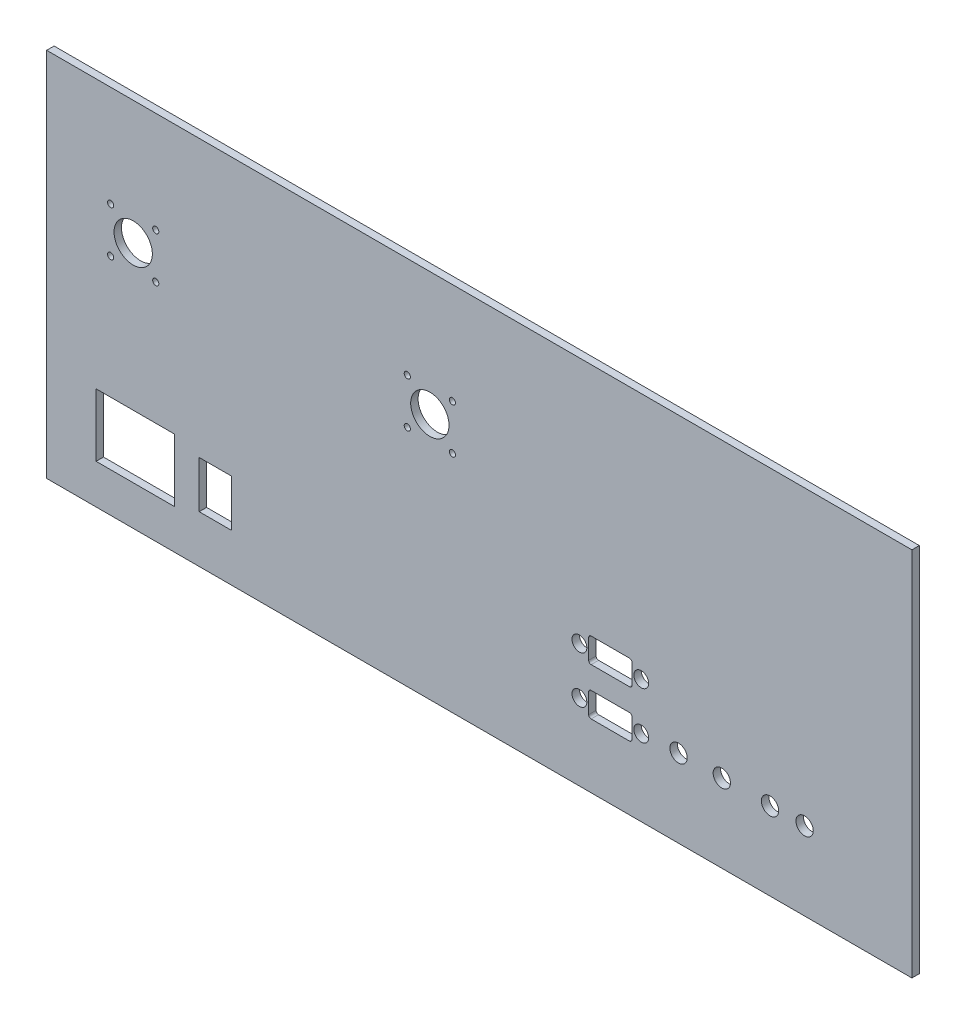
SolidWorks part; units mm, degrees
ref_plane "前视基准面" through (0, 0, 0) normal (0, 0, 1) x (1, 0, 0)
ref_plane "上视基准面" through (0, 0, 0) normal (0, 1, 0) x (1, 0, 0)
ref_plane "右视基准面" through (0, 0, 0) normal (1, 0, 0) x (0, 0, -1)
sketch "草图2" plane through (0, 0, 0) normal (0, 0, 1) x (1, 0, 0)
  line L4 (-175, 150) -> (-175, 0)
  line L5 (-175, 0) -> (175, 0)
  line L6 (175, 0) -> (175, 150)
  line L7 (175, 150) -> (-175, 150)
  line L8 (-175, 150) -> (-175, 0)
  line L9 (-175, 0) -> (175, 0)
  line L10 (175, 0) -> (175, 150)
  line L11 (175, 150) -> (-175, 150)
  dimension "D1" = 0
extrude "凸台-拉伸1" add sketch "草图2" along normal blind 3
sketch "草图3" plane through (0, 0, 3) normal (0, 0, 1) x (1, 0, 0)
  line L0 (37, 24.6) -> (137, 24.6) construction
  line L1 (-155, 28.7) -> (-106.8, 28.7) construction
  line L2 (36.8578, 25.7694) -> (54.3578, 35.7694) construction
  line L3 (110.1404, 30.9806) -> (-4.1371, 30.9806) construction
  line L4 (175, 150) -> (-175, 150)
  line L5 (-175, 150) -> (-175, 0)
  line L6 (-175, 0) -> (175, 0)
  line L7 (175, 0) -> (175, 150)
  line L8 (175, 150) -> (-175, 150) construction
  line L9 (-175, 150) -> (-175, 0) construction
  line L10 (-175, 0) -> (175, 0) construction
  line L11 (175, 0) -> (175, 150) construction
  line L12 (61.75, 45.925) -> (61.75, 53.925)
  line L13 (37, 24.6) -> (137, 24.6) construction
  line L14 (53, 24.6) -> (53, 50.5185) construction
  line L15 (110.1387, 30.875) -> (-4.1387, 30.875) construction
  line L16 (45.25, 25.875) -> (60.75, 25.875)
  line L17 (44.25, 26.875) -> (44.25, 34.875)
  line L18 (45.25, 35.875) -> (60.75, 35.875)
  line L19 (61.75, 26.875) -> (61.75, 34.875)
  line L20 (44.25, 25.875) -> (61.75, 35.875) construction
  line L21 (44.25, 35.875) -> (61.75, 25.875) construction
  line L22 (45.25, 54.925) -> (60.75, 54.925)
  line L23 (45.25, 44.925) -> (60.75, 44.925)
  line L28 (72.75, 24.6) -> (72.75, 34.6) construction
  line L29 (80.6, 24.6) -> (80.6, 31.6) construction
  line L30 (98.1, 24.6) -> (98.1, 31.6) construction
  line L31 (117.6, 24.6) -> (117.6, 31.6) construction
  line L32 (131.6, 24.6) -> (131.6, 31.6) construction
  line L33 (-140, 100) -> (-20, 100) construction
  line L34 (-155, 16) -> (-123.3, 16)
  line L35 (-155, 16) -> (-155, 41.4)
  line L36 (-155, 41.4) -> (-123.3, 41.4)
  line L37 (-123.3, 16) -> (-123.3, 41.4)
  line L38 (-149.12, 90.88) -> (-130.88, 90.88) construction
  line L39 (-149.12, 90.88) -> (-149.12, 109.12) construction
  line L40 (-149.12, 109.12) -> (-130.88, 109.12) construction
  line L41 (-130.88, 90.88) -> (-130.88, 109.12) construction
  line L42 (-149.12, 90.88) -> (-130.88, 109.12) construction
  line L43 (-149.12, 109.12) -> (-130.88, 90.88) construction
  line L44 (44.25, 45.925) -> (44.25, 53.925)
  line L46 (-113.3, 19.2) -> (-100.3, 19.2)
  line L47 (-113.3, 19.2) -> (-113.3, 38.2)
  line L48 (-113.3, 38.2) -> (-100.3, 38.2)
  line L49 (-100.3, 19.2) -> (-100.3, 38.2)
  line L50 (-113.3, 19.2) -> (-100.3, 38.2) construction
  line L51 (-113.3, 38.2) -> (-100.3, 19.2) construction
  arc A0 (60.75, 35.875) -> (61.75, 34.875) centre (60.75, 34.875) cw
  arc A1 (60.75, 25.875) -> (61.75, 26.875) centre (60.75, 26.875) ccw
  arc A2 (45.25, 25.875) -> (44.25, 26.875) centre (45.25, 26.875) cw
  arc A3 (44.25, 34.875) -> (45.25, 35.875) centre (45.25, 34.875) cw
  circle A4 centre (40.5, 30.875) radius 3
  circle A5 centre (65.5, 30.875) radius 3
  circle A12 centre (72.75, 34.6) radius 1.75 construction
  circle A13 centre (80.6, 31.6) radius 3.5
  circle A14 centre (98.1, 31.6) radius 3.5
  circle A15 centre (117.6, 31.6) radius 3.5
  circle A16 centre (131.6, 31.6) radius 3.5
  circle A17 centre (-149.12, 109.12) radius 1.25
  circle A18 centre (-130.88, 109.12) radius 1.25
  circle A19 centre (-149.12, 90.88) radius 1.25
  circle A20 centre (-130.88, 90.88) radius 1.25
  circle A21 centre (-140, 100) radius 7.75
  circle A22 centre (-29.12, 90.88) radius 1.25
  circle A23 centre (-10.88, 90.88) radius 1.25
  circle A24 centre (-20, 100) radius 7.75
  circle A25 centre (-29.12, 109.12) radius 1.25
  circle A26 centre (-10.88, 109.12) radius 1.25
  arc A27 (60.75, 54.925) -> (61.75, 53.925) centre (60.75, 53.925) cw
  arc A28 (45.25, 44.925) -> (44.25, 45.925) centre (45.25, 45.925) cw
  circle A29 centre (65.5, 49.925) radius 3
  arc A30 (44.25, 53.925) -> (45.25, 54.925) centre (45.25, 53.925) cw
  circle A31 centre (40.5, 49.925) radius 3
  arc A32 (60.75, 44.925) -> (61.75, 45.925) centre (60.75, 45.925) ccw
  point P8 (53, 30.875)
  point P9 (53, 30.875)
  point P14 (44.25, 30.875)
  point P27 (40.5, 30.875)
  point P30 (53, 30.875)
  point P31 (65.5, 30.875)
  point P36 (53, 49.925)
  point P37 (72.75, 24.6)
  point P42 (45.6078, 30.7694)
  point P45 (53.0017, 30.9806)
  point P76 (-140, 100)
  point P107 (-106.8, 19.2)
  dimension "D6" = 1
  dimension "D9" = 6
  dimension "D10" = 6
  dimension "D14" = 3.5
  dimension "D17" = 7
  dimension "D20" = 7
  dimension "D23" = 7
  dimension "D26" = 7
  dimension "D33" = 2.5
  dimension "D34" = 2.5
  dimension "D35" = 2.5
  dimension "D36" = 2.5
  dimension "D37" = 15.5
  dimension "D2" = 16
  dimension "D3" = 6.275
  dimension "D4" = 17.5
  dimension "D5" = 10
  dimension "D7" = 12.5
  dimension "D8" = 12.5
  dimension "D11" = 19.05
  dimension "D12" = 35.75
  dimension "D13" = 10
  dimension "D15" = 43.6
  dimension "D16" = 7
  dimension "D18" = 7
  dimension "D19" = 61.1
  dimension "D21" = 7
  dimension "D22" = 80.6
  dimension "D24" = 7
  dimension "D25" = 94.6
  dimension "D27" = 31.7
  dimension "D28" = 25.4
  dimension "D29" = 20
  dimension "D30" = 16
  dimension "D31" = 18.24
  dimension "D32" = 18.24
  dimension "D38" = 100
  dimension "D39" = 35
  dimension "D40" = 120
  dimension "D41" = 19
  dimension "D42" = 13
  dimension "D43" = 10
  dimension "D1" = 0
extrude "切除-拉伸1" cut sketch "草图3" against normal through all
equation "\"D18@草图3\"=\"D16@草图3\""
equation "\"D20@草图3\"=\"D17@草图3\""
equation "\"D21@草图3\"=\"D16@草图3\""
equation "\"D23@草图3\"=\"D17@草图3\""
equation "\"D24@草图3\"=\"D16@草图3\""
equation "\"D26@草图3\"=\"D17@草图3\""
equation "\"D32@草图3\"=\"D31@草图3\""
equation "\"D34@草图3\"=\"D33@草图3\""
equation "\"D35@草图3\"=\"D33@草图3\""
equation "\"D36@草图3\"=\"D33@草图3\""
